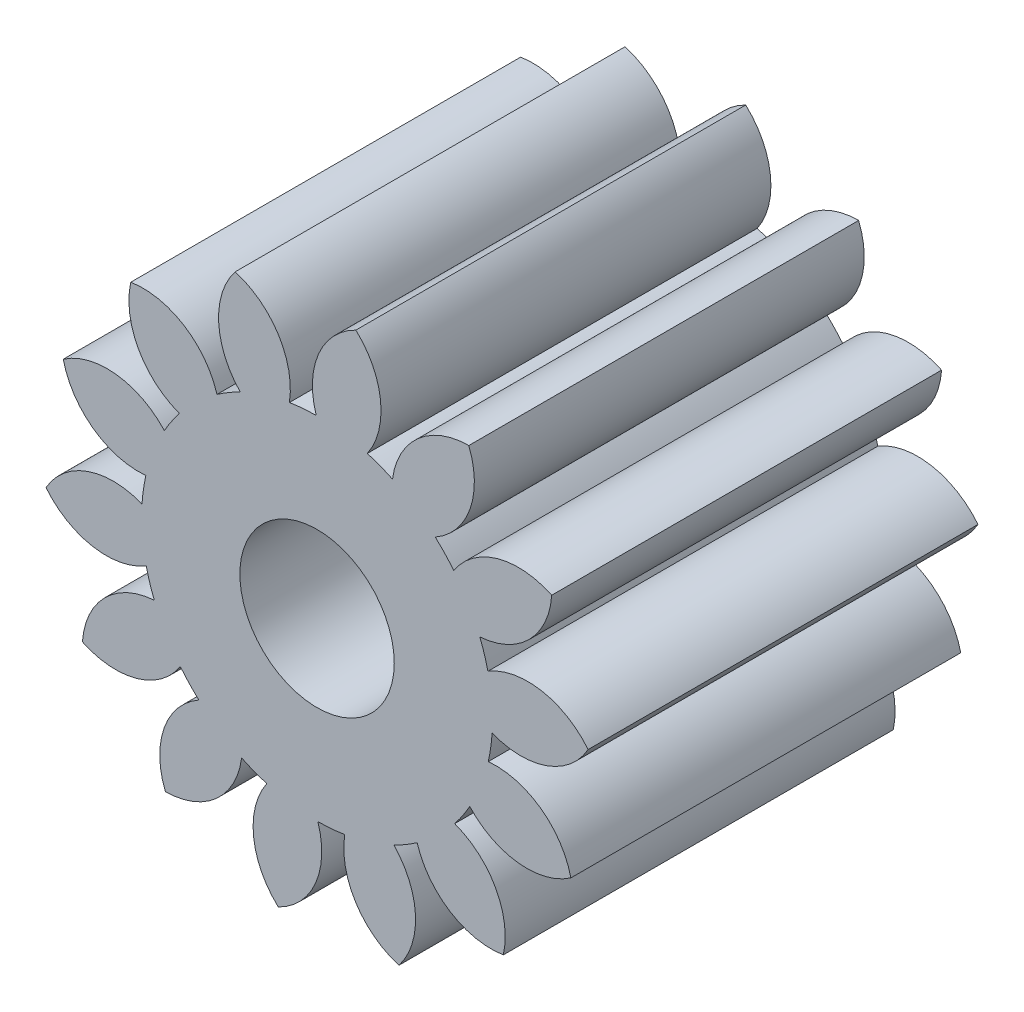
SolidWorks part; units mm, degrees
ref_plane "Alzado" through (0, 0, 0) normal (0, 0, 1) x (1, 0, 0)
ref_plane "Planta" through (0, 0, 0) normal (0, 1, 0) x (1, 0, 0)
ref_plane "Vista lateral" through (0, 0, 0) normal (1, 0, 0) x (0, 0, -1)
sketch "Croquis1" plane through (0, 0, 0) normal (0, 0, 1) x (1, 0, 0)
  circle A0 centre (0, 0) radius 3.5
  circle A1 centre (0, 0) radius 0.99
  dimension "D1" = 7
  dimension "D2" = 1.98
extrude "Saliente-Extruir1" add sketch "Croquis1" along normal blind 5
sketch "Croquis2" plane through (0, 0, 5) normal (0, 0, 1) x (1, 0, 0)
  line L0 (0, 0) -> (0, 6.1329) construction
  line L1 (0, 0) -> (2.1618, 5.9395) construction
  line L2 (0, 2.9) -> (0.932, 2.5608) construction
  line L3 (0, 0) -> (-0.5, 6.1329) construction
  circle A0 centre (0, 0) radius 3.5
  circle A1 centre (0, 0) radius 2.9
  circle A2 centre (0, 0) radius 2.25
  circle A3 centre (0.932, 2.5608) radius 0.9919
  circle A4 centre (-1.3345, 2.376) radius 0.9919
  dimension "D1" = 4.5
  dimension "D2" = 5.8
  dimension "D5" = 7
  dimension "D3" = 20
  dimension "D4" = 0.5
extrude "Cortar-Extruir1" cut sketch "Croquis2" against normal blind 5 contours A0 A4 A1 A3 | A1 A4 A2 A3
pattern_circular "MatrizC1" count 14 over 360 about axis through (0, 0, 0) along (0, 0, 1) of "Cortar-Extruir1"
